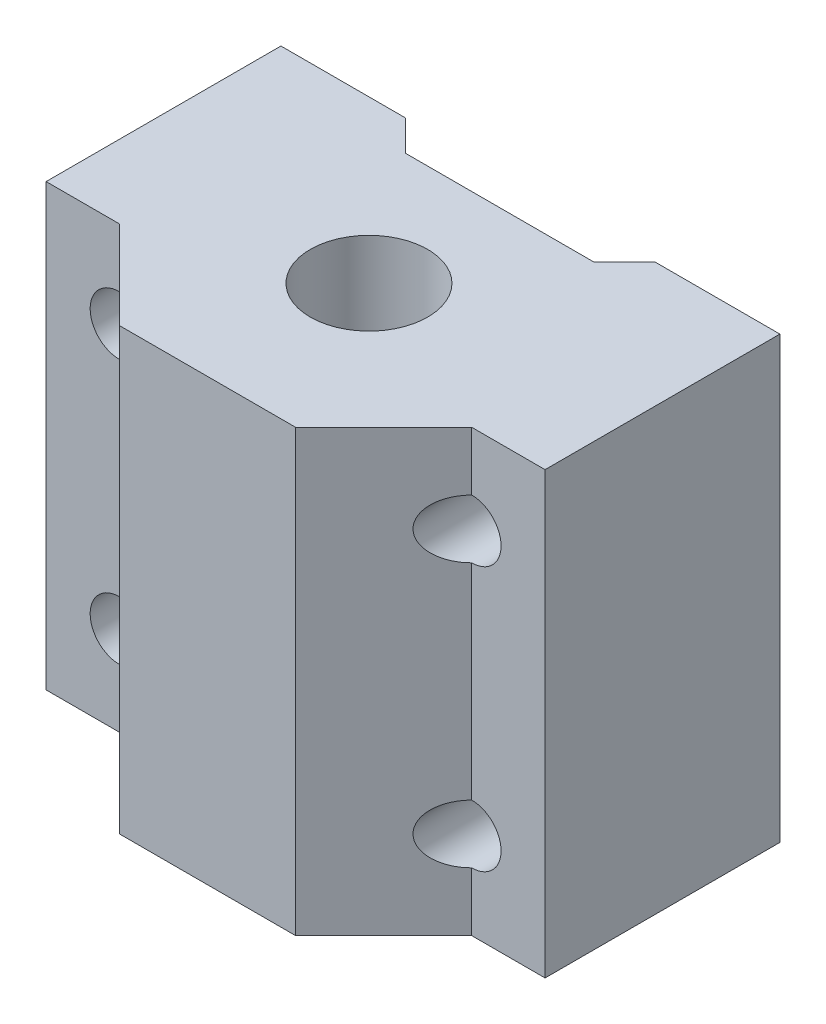
SolidWorks part; units mm, degrees
ref_plane "Front Plane" through (0, 0, 0) normal (0, 0, 1) x (1, 0, 0)
ref_plane "Top Plane" through (0, 0, 0) normal (0, 1, 0) x (1, 0, 0)
ref_plane "Right Plane" through (0, 0, 0) normal (1, 0, 0) x (0, 0, -1)
sketch "Sketch1" plane through (0, 0, 0) normal (0, 0, 1) x (1, 0, 0)
  line L0 (-12, 15) -> (-12, -15) construction
  line L1 (-17, -15) -> (17, -15)
  line L2 (-17, -15) -> (-17, 15)
  line L3 (-17, 15) -> (17, 15)
  line L4 (17, -15) -> (17, 15)
  line L5 (-17, -15) -> (17, 15) construction
  line L6 (-17, 15) -> (17, -15) construction
  line L7 (12, 15) -> (12, -15) construction
  line L8 (-17, 9) -> (17, 9) construction
  line L9 (-17, -9) -> (17, -9) construction
  line L10 (-17, -9) -> (17, 9) construction
  circle A0 centre (-12, 9) radius 2
  circle A1 centre (-12, -9) radius 2
  circle A2 centre (12, 9) radius 2
  circle A3 centre (12, -9) radius 2
  point P0 (0, 0)
  point P15 (0, 0)
  dimension "D6" = 4
  dimension "D1" = 34
  dimension "D2" = 30
  dimension "D3" = 24
  dimension "D4" = 5
  dimension "D5" = 18
extrude "Boss-Extrude1" add sketch "Sketch1" along normal blind 22
sketch3d "3DSketch1"
  point P0 (-10.3322, 15, 5.266)
ref_plane "Plane1" through (0, 15, 0) normal (0, 1, 0) x (1, 0, 0)
sketch "Sketch3" plane through (0, 15, 0) normal (0, 1, 0) x (1, 0, 0)
  line L0 (-17, -11) -> (17, -11) construction
  line L1 (-17, -22) -> (-17, 0) construction
  line L2 (17, -22) -> (17, 0) construction
  line L3 (0, 0) -> (0, -22) construction
  line L4 (17, -22) -> (-17, -22) construction
  line L5 (-17, -16) -> (-12, -16)
  line L6 (-17, -16) -> (-17, -22)
  line L7 (-12, -16) -> (-6, -22)
  line L8 (-17, -22) -> (-6, -22)
  line L9 (17, -22) -> (6, -22)
  line L10 (17, -16) -> (17, -22)
  line L11 (17, -16) -> (12, -16)
  line L12 (12, -16) -> (6, -22)
  line L13 (-8.5, 0) -> (8.5, 0) construction
  line L14 (-8.5, 0) -> (-6.4149, -2.0851)
  line L15 (8.5, 0) -> (6.4149, -2.0851)
  line L16 (-6.4149, -2.0851) -> (6.4149, -2.0851)
  line L17 (17, 0) -> (-17, 0) construction
  line L18 (-17, 0) -> (17, 0) construction
  line L19 (-6.4149, -2.0851) -> (8.5, 0) construction
  line L20 (-8.5, 0) -> (6.4149, -2.0851) construction
  line L21 (-8.5, 0) -> (8.5, 0)
  circle A0 centre (0, -11) radius 4
  point P33 (0, -1.1883)
  dimension "D1" = 8
  dimension "D2" = 135
  dimension "D3" = 6
  dimension "D4" = 5
  dimension "D5" = 135
  dimension "D6" = 135
  dimension "D7" = 45
  dimension "D8" = 3.5
  dimension "D9" = 3.5
  dimension "D10" = 12.8298
extrude "Cut-Extrude1" cut sketch "Sketch3" against normal blind 30
